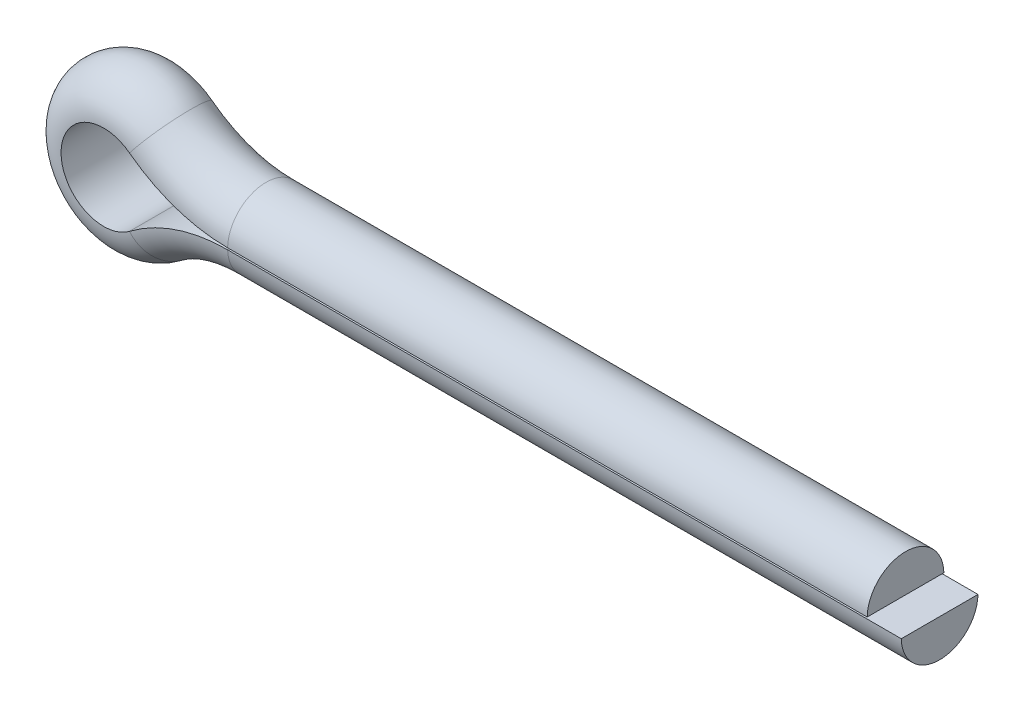
SolidWorks part; units mm, degrees
ref_plane "Front" through (0, 0, 0) normal (0, 0, 1) x (1, 0, 0)
ref_plane "Top" through (0, 0, 0) normal (0, 1, 0) x (1, 0, 0)
ref_plane "Right" through (0, 0, 0) normal (1, 0, 0) x (0, 0, -1)
sketch "Sketch1" plane through (0, 0, 0) normal (0, 0, 1) x (1, 0, 0)
  line L0 (-22.7412, 0) -> (1.016, 0) construction
  line L1 (-19.05, -0.0254) -> (1.016, -0.0254)
  line L2 (-21.4715, 0.0254) -> (1.016, 0.0254) construction
  line L3 (-19.05, 0.0254) -> (0, 0.0254)
  line L4 (-11.4985, 0.0254) -> (1.016, 0.0254) construction
  line L5 (-11.4985, -0.0254) -> (1.016, -0.0254) construction
  line L6 (-22.7412, 1.2065) -> (-22.7412, 0) construction
  line L7 (-22.7412, 1.2065) -> (-22.7412, 2.413) construction
  line L8 (-11.4985, 0) -> (1.016, 0) construction
  line L9 (0, 0.0254) -> (0, 0) construction
  line L10 (-22.7412, 0) -> (-22.7412, -2.413) construction
  line L11 (-19.05, 1.1176) -> (-19.05, -1.1684) construction
  arc A1 (-21.9722, 1.0107) -> (-21.9722, -1.0107) centre (-22.7412, 0) ccw
  arc A2 (-19.05, -0.0254) -> (-21.9722, -1.0107) centre (-19.05, -4.8514) ccw
  arc A3 (-21.9722, 1.0107) -> (-19.05, 0.0254) centre (-19.05, 4.8514) ccw
  circle A4 centre (-22.7412, 0) radius 2.413 construction
  point P15 (0, 0.0254)
  point P26 (-19.05, -0.0254)
  dimension "D6" = 4.826
  dimension "ExtendedProngLength" = 1.016
  dimension "Length" = 19.05
  dimension "Diameter" = 2.286
  dimension "Head Diameter" = 4.826
  dimension "D1" = 1.143
  dimension "D4" = 0.0254
  dimension "D5" = 0.0254
sketch "Sketch2" plane through (0, 0, 0) normal (1, 0, 0) x (0, 0, -1)
  line L0 (-1.1427, 0.0254) -> (1.1427, 0.0254)
  line L1 (0, 1.143) -> (0, -1.143) construction
  circle A1 centre (0, 0) radius 1.143 construction
  arc A2 (-1.1427, 0.0254) -> (1.1427, 0.0254) centre (0, 0) cw
  point P5 (0, 0)
  dimension "WireWidth" = 2.286
sketch "Sketch3" plane through (0, 0, 0) normal (0, 0, 1) x (1, 0, 0)
  line L0 (-19.05, 0.0254) -> (0, 0.0254) construction
  line L1 (-19.05, -0.0254) -> (1.016, -0.0254) construction
  line L2 (-19.05, 0.0254) -> (0, 0.0254)
  line L3 (-19.05, -0.0254) -> (1.016, -0.0254)
  arc A0 (-19.05, -0.0254) -> (-21.9722, -1.0107) centre (-19.05, -4.8514) ccw construction
  arc A1 (-21.9722, 1.0107) -> (-21.9722, -1.0107) centre (-22.7412, 0) ccw construction
  arc A2 (-21.9722, 1.0107) -> (-19.05, 0.0254) centre (-19.05, 4.8514) ccw construction
  arc A3 (-19.05, -0.0254) -> (-21.9722, -1.0107) centre (-19.05, -4.8514) ccw
  arc A4 (-21.9722, 1.0107) -> (-21.9722, -1.0107) centre (-22.7412, 0) ccw
  arc A5 (-21.9722, 1.0107) -> (-19.05, 0.0254) centre (-19.05, 4.8514) ccw
sketch "Sketch4" plane through (0, 0, 0) normal (1, 0, 0) x (0, 0, -1)
  line L0 (-1.1427, 0.0254) -> (1.1427, 0.0254) construction
  line L1 (-1.1427, 0.0254) -> (1.1427, 0.0254)
  arc A2 (1.1427, 0.0254) -> (-1.1427, 0.0254) centre (0, 0) ccw construction
  arc A3 (1.1427, 0.0254) -> (-1.1427, 0.0254) centre (0, 0) ccw
sweep "Sweep1" add profiles "Sketch4" path "Sketch3"
equation "\"WireWidth@Sketch2\"=\"Diameter@Sketch1\""
equation "\"D1@Sketch1\"=\"Diameter@Sketch1\"/2"
